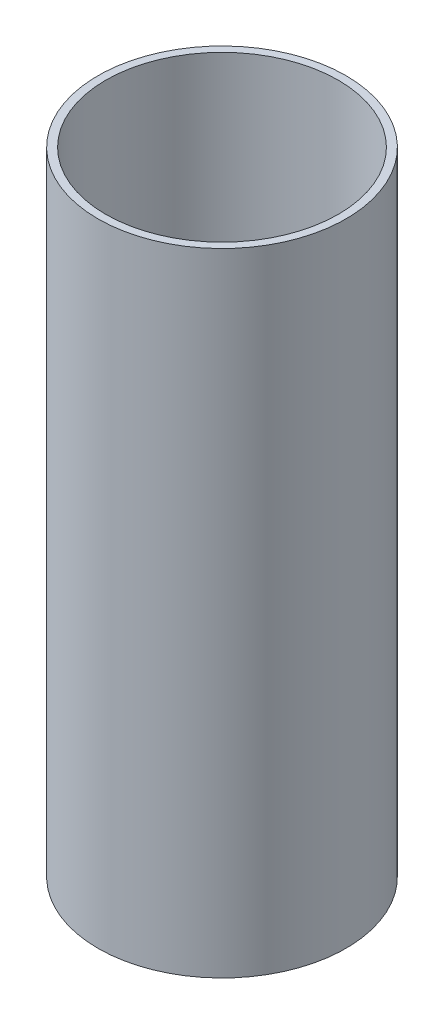
SolidWorks part; units mm, degrees
ref_plane "Front Plane" through (0, 0, 0) normal (0, 0, 1) x (1, 0, 0)
ref_plane "Top Plane" through (0, 0, 0) normal (0, 1, 0) x (1, 0, 0)
ref_plane "Right Plane" through (0, 0, 0) normal (1, 0, 0) x (0, 0, -1)
sketch "Sketch1" plane through (0, 0, 0) normal (0, 1, 0) x (1, 0, 0)
  circle A0 centre (0, 0) radius 37.3971
  circle A1 centre (0, 0) radius 39.8971
  dimension "D1" = 74.7942
  dimension "D2" = 2.5
extrude "Boss-Extrude1" add sketch "Sketch1" along normal blind 203.2
equation "\"Reservoir Capacity\"= 750'mL"
equation "\"Reservoir Height\"= 8 * 2.54'cm"
equation "\"Reservoir Radius\"= \"Reservoir Capacity\" / \"Reservoir Height\" / ( PI ^ 2 )'cm"
equation "\"Reservoir Thickness\"= 0.25'cm"
equation "\"D1@Sketch1\"= \"Reservoir Radius\" * 2"
equation "\"D2@Sketch1\"=\"Reservoir Thickness\""
equation "\"D1@Boss-Extrude1\"=\"Reservoir Height\""
